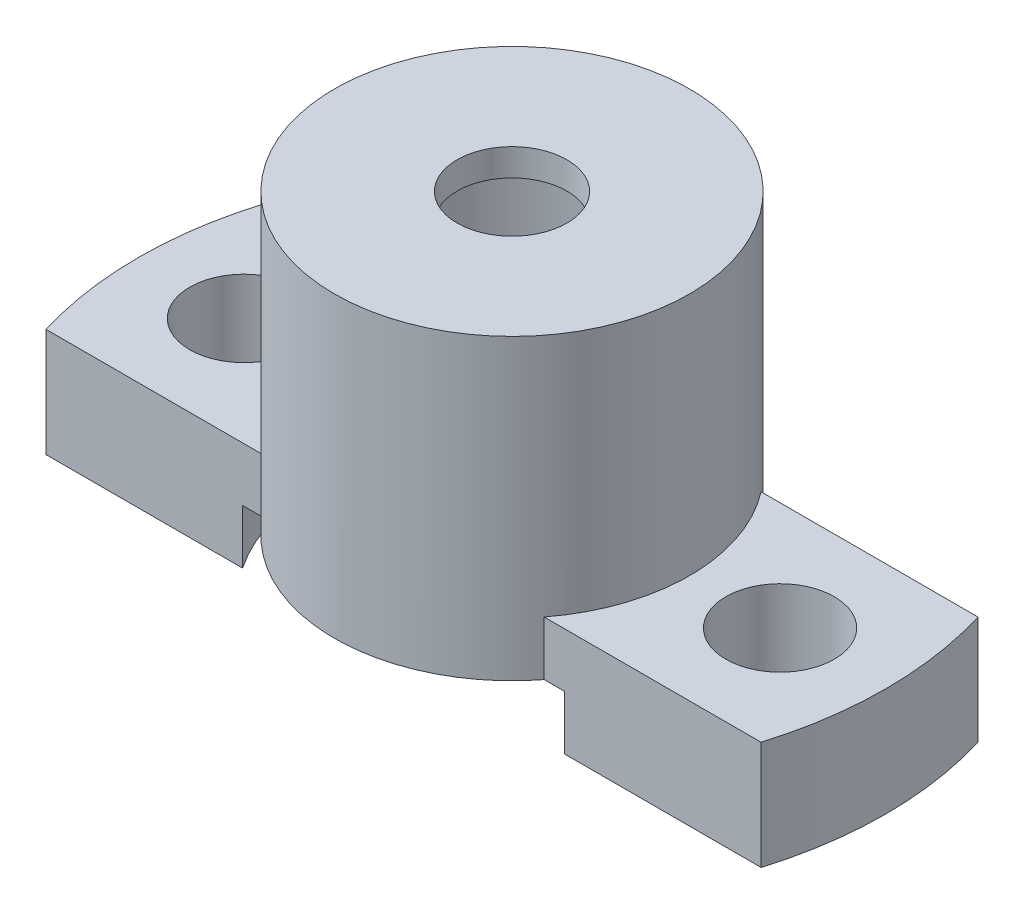
SolidWorks part; units mm, degrees
ref_plane "Front Plane" through (0, 0, 0) normal (0, 0, 1) x (1, 0, 0)
ref_plane "Top Plane" through (0, 0, 0) normal (0, 1, 0) x (1, 0, 0)
ref_plane "Right Plane" through (0, 0, 0) normal (1, 0, 0) x (0, 0, -1)
sketch "..." plane through (0, 0, 0) normal (0, 1, 0) x (1, 0, 0)
  circle A0 centre (0, 0) radius 5.55
  circle A1 centre (0, 0) radius 6.55
  dimension "D2" = 11.1
  dimension "D1" = 1
sketch "Sketch5" plane through (0, 0, 0) normal (0, 1, 0) x (-1, 0, 0)
  circle A0 centre (0, 0) radius 6.55
  circle A1 centre (0, 0) radius 2.025
  dimension "D1" = 4.05
  dimension "D2" = 13.1
extrude "Ext_TopMagnetRoom" add sketch "Sketch5" along normal blind 1
sketch "Sketch7" plane through (0, 0, 0) normal (0, -1, 0) x (1, 0, 0)
  circle A0 centre (0, 0) radius 5.05
  circle A1 centre (0, 0) radius 6.55
  circle A3 centre (0, 0) radius 6.55 construction
  dimension "D1" = 10.1
extrude "Ext_MagnetRoom" add sketch "Sketch7" along normal blind 4
sketch "Sketch6" plane through (0, -4, 0) normal (0, -1, 0) x (1, 0, 0)
  line L0 (13.1868, -4) -> (5.1868, -4)
  line L1 (-13.1868, -4) -> (-5.1868, -4)
  line L2 (-13.1868, 4) -> (-5.1868, 4)
  line L3 (5.1868, 4) -> (13.1868, 4)
  line L4 (13.7801, 0) -> (6.55, 0) construction
  line L5 (6.55, 0) -> (0, 0) construction
  line L6 (0, 0) -> (-6.55, 0) construction
  line L7 (-6.55, 0) -> (-13.7801, 0) construction
  line L10 (13.1868, -4) -> (13.1868, 4) construction
  arc A0 (13.1868, 4) -> (13.1868, -4) centre (0, 0) cw
  arc A1 (-13.1868, -4) -> (-13.1868, 4) centre (0, 0) cw
  arc A2 (5.1868, -4) -> (5.1868, 4) centre (0, 0) ccw
  arc A3 (-5.1868, -4) -> (-5.1868, 4) centre (0, 0) cw
  circle A4 centre (0, 0) radius 6.55 construction
extrude "Bottom-arms fixing with support" add sketch "Sketch6" against normal blind 2
sketch "Sketch9" plane through (0, -4, 0) normal (0, -1, 0) x (1, 0, 0)
  line L0 (13.1868, 4) -> (5.9368, 4)
  line L1 (13.1868, 4) -> (5.1868, 4) construction
  line L2 (-13.1868, -4) -> (-5.9368, -4)
  line L3 (-13.1868, -4) -> (-5.1868, -4) construction
  line L4 (-13.1868, 4) -> (-5.9368, 4)
  line L5 (13.1868, -4) -> (5.9368, -4)
  line L6 (-5.1868, 4) -> (-13.1868, 4) construction
  line L7 (5.1868, -4) -> (13.1868, -4) construction
  line L8 (-5.9368, 4) -> (-5.1868, 4) construction
  arc A1 (-13.1868, -4) -> (-13.1868, 4) centre (0, 0) cw
  arc A2 (13.1868, 4) -> (13.1868, -4) centre (0, 0) cw
  arc A3 (-5.9368, -4) -> (-5.9368, 4) centre (0, 0) cw
  arc A4 (5.9368, 4) -> (5.9368, -4) centre (0, 0) cw
  circle A5 centre (0, 0) radius 6.55 construction
  dimension "D1" = 0.75
extrude "Bottom- Fixing arms End" add sketch "Sketch9" along normal blind 2
sketch "Esquisse1" plane through (0, -2, 0) normal (0, 1, 0) x (1, 0, 0)
  circle A0 centre (-9.8868, 0) radius 2
  circle A1 centre (9.8868, 0) radius 2
  circle A4 centre (-9.8868, 0) radius 2.25 construction
  circle A5 centre (9.8868, 0) radius 2.25 construction
  dimension "D1" = 4
extrude "Ext_HoleMounted" cut sketch "Esquisse1" against normal through all
sketch "Sketch10" plane through (0, 1, 0) normal (0, 1, 0) x (1, 0, 0)
  circle A0 centre (0, 0) radius 5.05
  circle A1 centre (0, 0) radius 6.55
  circle A3 centre (0, 0) radius 5.05 construction
  circle A4 centre (0, 0) radius 6.55 construction
extrude "chamber" add sketch "Sketch10" along normal blind 5
sketch "Sketch11" plane through (0, 6, 0) normal (0, 1, 0) x (1, 0, 0)
  circle A0 centre (0, 0) radius 6.55
  circle A1 centre (0, 0) radius 2.025
  circle A3 centre (0, 0) radius 6.55 construction
  circle A6 centre (0, 0) radius 2.025 construction
extrude "Boss-Extrude4" add sketch "Sketch11" along normal blind 1
sketch "Esquisse2" [suppressed] plane through (0, 0, 0) normal (0, 0, 1) x (1, 0, 0)
  line L1 (26.7806, 17.3131) -> (-24.7319, 17.3131)
  line L2 (26.7806, 17.3131) -> (26.7806, -15.9722)
  line L3 (26.7806, -15.9722) -> (-24.7319, -15.9722)
  line L4 (-24.7319, 17.3131) -> (-24.7319, -15.9722)
extrude "Enlèv. mat.-Extru.1" [suppressed] cut sketch "Esquisse2" along normal through all
sketch "Esquisse3" plane through (0, -2, 0) normal (0, 1, 0) x (1, 0, 0)
  circle A0 centre (9.8868, 0) radius 3
  circle A1 centre (-9.8868, 0) radius 3
  circle A2 centre (9.8868, 0) radius 2 construction
  arc A3 (-11.4876, -1.1989) -> (-11.4876, 1.1989) centre (-9.8868, 0) ccw construction
  dimension "D1" = 1
extrude "Enlèv. mat.-Extru.2" cut sketch "Esquisse3" along normal through all
sketch "Sketch12" plane through (0, -6, 0) normal (0, -1, 0) x (1, 0, 0)
  circle A0 centre (-9.8868, 0) radius 2.5
  circle A1 centre (9.8868, 0) radius 2.5
  dimension "D1" = 5
  dimension "D2" = 5
extrude "Cut-Extrude1" [suppressed] cut sketch "Sketch12" against normal blind 10
sketch "Sketch13" plane through (0, -4, 0) normal (0, -1, 0) x (1, 0, 0)
  circle A0 centre (0, 0) radius 5.2
  dimension "D1" = 10.4
extrude "Cut-Extrude2" cut sketch "Sketch13" against normal up to surface (4 mm away) up to face at (0, 0, 2.025)
equation "\"magnet_DI\"= 3mm'inner diameter of the o-ring magnet"
equation "\"magnet_DE\"= 8mm'external diameter of the o-ring magnet"
equation "\"magnet_H\"= 3mm'tall of the magnet"
equation "\"magnet_levitation_DI\"= 0mm'inner diameter of the o-ring magnet"
equation "\"magnet_levitation_DE\"= 1mm'external diameter of the o-ring magnet"
equation "\"magnet_levitation_H\"= 0.5mm'tall of the magnet"
equation "\"gap_magnet_H\"= 1mm'gap between the 2 magnets"
equation "\"plug_DI\"= 1.5mm'size of the inner extrude of the plug (finger contact)"
equation "\"coil_H\"= 8mm 'height coil"
equation "\"coil_W\"= 0.2mm 'width coil"
equation "\"mandrine_freegap\"= 0.2mm 'gap between the magnet and the mandrine. "
equation "\"mandrine_bottom_H\"= 0.5mm 'border of the bottom of the mandrine"
equation "\"mandrine_coilmagnet_wall\"= 0.15mm"
equation "\"mandrine_magnet_lev\"= 3mm' gap needed for the levitation of the rod"
equation "\"mandrine_border_H\"= 2mm 'border of the top of the mandrine"
equation "\"mandrine_epoxy_W\"= 0.5mm 'width epoxy"
equation "\"mandrine_DI\"= \"mandrine_freegap\"*2+\"magnet_DE\""
equation "\"mandrine_DE\"= (\"mandrine_epoxy_W\"+\"coil_W\"+\"mandrine_coilmagnet_wall\")*2+\"mandrine_DI\""
equation "\"mandrine_H\"= \"magnet_levitation_H\"+\"mandrine_magnet_lev\"+\"magnet_H\"+\"gap_magnet_H\"/2+\"coil_H\"/2+\"mandrine_border_H\""
equation "\"mandrine_hat_W\"= 1mm"
equation "\"tower_freegap\"= 1mm 'gap between the actuator and the tower"
equation "\"tower_DI\"= \"mandrine_DE\"+\"tower_freegap\""
equation "\"tower_W\"= 1mm'width of the tower"
equation "\"tower_link_H\"= 2mm"
equation "\"tower_link_W\"= 4mm"
equation "\"tower_channel_W\"= 1mm"
equation "\"tower_renforcement_H\"= 2mm"
equation "\"apex_tower_Dbase\"= 2.5mm 'diameter of the holes in order to curve"
equation "\"apex_tower_Rbase1\"= 0.75mm 'diameter of the holes in order to curve"
equation "\"apex_tower_Rbase2\"= 1mm 'diameter of the holes in order to curve"
equation "\"apex_tower_Rbase3\"= 1.25mm 'diameter of the holes in order to curve"
equation "\"apex_tower_holeOpening1\"= \"apex_tower_Rbase1\"*7/8"
equation "\"apex_tower_holeOpening2\"= \"apex_tower_Rbase2\"*7/8"
equation "\"apex_tower_holeOpening3\"= \"apex_tower_Rbase3\"*7/8"
equation "\"apex_tower_Hbase\"= 1mm 'gap between the bottom of the tower and the holes"
equation "\"apex_tower_hole\"= 4.5mm 'witdh of the hole"
equation "\"apex_tower_H\"= 0mm '\"mandrine_H\"-\"tower_link_H\""
equation "\"apex_tower_H2\"= \"apex_tower_H\"+7mm"
equation "\"actuator1.x\"= 42.59mm"
equation "\"actuator2.x\"= 80.026mm"
equation "\"actuator3.x\"= 0mm"
equation "\"actuator4.x\"= 14.55mm"
equation "\"actuator5.x\"= 14.557mm"
equation "\"actuator6.x\"= 12.497mm"
equation "\"actuator7.x\"= 27.494mm"
equation "\"actuator8.x\"= 39.75mm"
equation "\"actuator9.x\"= 41.5767mm"
equation "\"actuator10.x\"= 41.148mm"
equation "\"actuator11.x\"= 70.869mm"
equation "\"actuator12.x\"= 77.15mm"
equation "\"actuator13.x\"= 70.87mm"
equation "\"actuator14.x\"= 80.15mm"
equation "\"actuator15.x\"= 92.21mm"
equation "\"actuator16.x\"= 97.61mm"
equation "\"actuator17.x\"= 87.41mm"
equation "\"actuator18.x\"= 109.08mm"
equation "\"actuator19.x\"= 125.04mm"
equation "\"actuator20.x\"= 119.466mm"
equation "\"actuator21.x\"= 115.558mm"
equation "\"actuator22.x\"= 142.74mm"
equation "\"actuator23.x\"= 145.93mm"
equation "\"actuator24.x\"= 131.11mm"
equation "\"actuator1.y\"= 101.167mm"
equation "\"actuator2.y\"= 120.647mm"
equation "\"actuator3.y\"= 45.677mm"
equation "\"actuator4.y\"= 66.047mm"
equation "\"actuator5.y\"= 45.327mm"
equation "\"actuator6.y\"= 28.807mm"
equation "\"actuator7.y\"= 13.807mm"
equation "\"actuator8.y\"= 30.087mm"
equation "\"actuator9.y\"= 49.157mm"
equation "\"actuator10.y\"= 71.787mm"
equation "\"actuator11.y\"= 78.407mm"
equation "\"actuator12.y\"= 52.377mm"
equation "\"actuator13.y\"= 25.793mm"
equation "\"actuator14.y\"= 0.711mm"
equation "\"actuator15.y\"= 34.092mm"
equation "\"actuator16.y\"= 57.427mm"
equation "\"actuator17.y\"= 86.987mm"
equation "\"actuator18.y\"= 92.077mm"
equation "\"actuator19.y\"= 63.187mm"
equation "\"actuator20.y\"= 34.434mm"
equation "\"actuator21.y\"= 0mm"
equation "\"actuator22.y\"= 38.901mm"
equation "\"actuator23.y\"= 70.278mm"
equation "\"actuator24.y\"= 100.8741mm"
equation "\"actuator1.z\"= 45.834mm"
equation "\"actuator2.z\"= 37.834mm"
equation "\"actuator3.z\"= 13mm"
equation "\"actuator4.z\"= 33.9226mm"
equation "\"actuator5.z\"= 51.234mm"
equation "\"actuator6.z\"= 29.9773mm"
equation "\"actuator7.z\"= 49.434mm"
equation "\"actuator8.z\"= 31.7209mm"
equation "\"actuator9.z\"= 60.084mm"
equation "\"actuator10.z\"= 45.3632mm"
equation "\"actuator11.z\"= 42.0948mm"
equation "\"actuator12.z\"= 33.6927mm"
equation "\"actuator13.z\"= 48.7255mm"
equation "\"actuator14.z\"= 45.0141mm"
equation "\"actuator15.z\"= 63.034mm"
equation "\"actuator16.z\"= 50.5713mm"
equation "\"actuator17.z\"= 61.634mm"
equation "\"actuator18.z\"= 46.3531mm"
equation "\"actuator19.z\"= 57.834mm"
equation "\"actuator20.z\"= 58.534mm"
equation "\"actuator21.z\"= 44.984mm"
equation "\"actuator22.z\"= 45.5969mm"
equation "\"actuator23.z\"= 42.2671mm"
equation "\"actuator24.z\"= 33.4578mm"
equation "\"shape_freegap\"= \"tower_freegap\""
equation "\"shape_strip_witdh\"= 5mm"
equation "\"shape_holes_sweat_D\"= 2mm"
equation "\"shape_holes_actuator_D\"= \"magnet_DE\"+\"shape_freegap\"+1mm"
equation "\"shape_holes_actuator_extD\"= \"shape_holes_actuator_D\"+2*\"shape_strip_witdh\""
equation "\"shape_holes_wet_D\"= 2mm"
equation "\"amortisseur_Dext\"= 18mm"
equation "\"amortisseur_Din\"= 7mm"
equation "\"amortisseur_H\"= 20mm"
equation "\"amortisseur_prise_D\"= 10mm"
equation "\"amortisseur_bourlet_H\"= 0.5mm"
equation "\"fixation_prise_base_D\"= (\"amortisseur_prise_D\"+3)"
equation "\"fixation_prise_base_H\"= 1mm"
equation "\"fixation_prise_tete_D\"= (\"amortisseur_Dext\"+3)"
equation "\"fixation_prise_tete_H\"= 2.5mm"
equation "\"fixation_D\"= \"fixation_prise_tete_D\" + 2mm"
equation "\"fixation_H\"= \"fixation_prise_base_H\" + \"fixation_prise_tete_H\" + 3mm"
equation "\"fixation_zone_accroche_D\"= 3*\"fixation_D\""
equation "\"oring_R\"= 0.75mm"
equation "\"oring_R1\"= 0.25mm"
equation "\"oring_R2\"= 0.3mm"
equation "\"oring_R3\"= 0.75mm"
equation "\"guide_H1\"=4mm"
equation "\"guide_H2\"=1mm"
equation "\"guide_W1\"=1mm"
equation "\"guide_openAngle\"=360deg"
equation "\"guide_ecrou_DI\"=5mm"
equation "\"guide_ecrou_DE\"=8mm"
equation "\"guide_vis_DI\"=4mm"
equation "\"guide_rondelle_DE\"=9mm"
equation "\"D1@...\" = \"guide_W1\""
equation "\"D2@...\" = \"tower_DI\""
equation "\"D2@Sketch5\"=\"tower_DI\"+\"tower_W\"*2"
equation "\"D1@Sketch5\"=\"magnet_DI\"+1.05"
equation "\"D1@Ext_TopMagnetRoom\" = \"guide_W1\""
equation "\"D1@Ext_MagnetRoom\" = \"guide_H1\""
equation "\"D1@Sketch7\"=\"mandrine_DE\""
